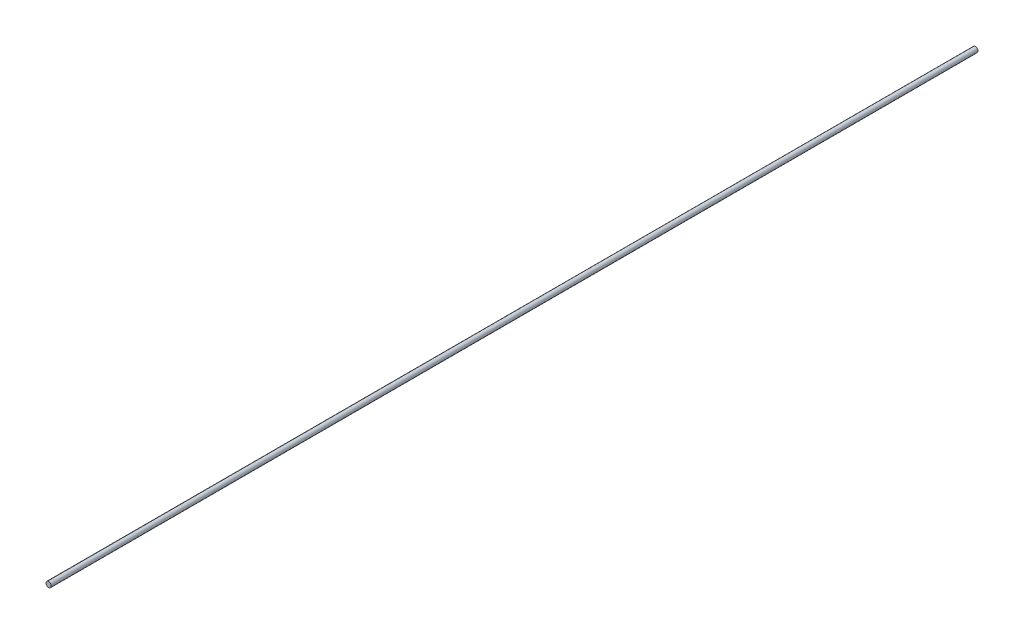
SolidWorks part; units mm, degrees
material "3.0205 (EN-AW 1200)"
ref_plane "Front Plane" through (0, 0, 0) normal (0, 0, 1) x (1, 0, 0)
ref_plane "Top Plane" through (0, 0, 0) normal (0, 1, 0) x (1, 0, 0)
ref_plane "Right Plane" through (0, 0, 0) normal (1, 0, 0) x (0, 0, -1)
sketch "Sketch1" plane through (0, 0, 0) normal (0, 0, 1) x (1, 0, 0)
  circle A0 centre (0, 0) radius 12.7
  dimension "D1" = 25.4
extrude "Boss-Extrude1" add sketch "Sketch1" along normal blind 4488.434 contours A0
equation "\"def\"= .009in"
equation "\"F\"= 400"
equation "\"E\"= 10000000"
equation "\"d\"= 1in"
equation "\"Area\"= pi * ( \"d\" ^ 2 ) / 4"
equation "\"Length\"= ( \"def\" * \"Area\" * \"E\" ) / \"F\""
